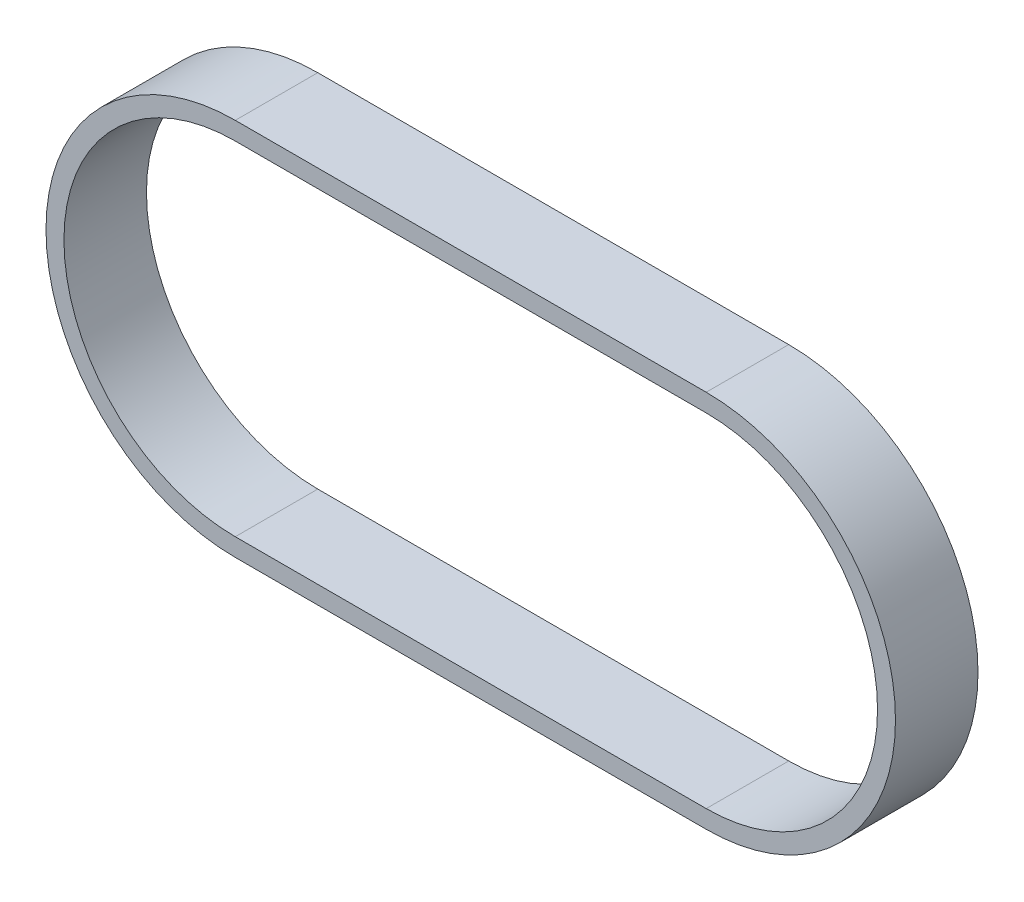
SolidWorks part; units mm, degrees
ref_plane "Front Plane" through (0, 0, 0) normal (0, 0, 1) x (1, 0, 0)
ref_plane "Top Plane" through (0, 0, 0) normal (0, 1, 0) x (1, 0, 0)
ref_plane "Right Plane" through (0, 0, 0) normal (1, 0, 0) x (0, 0, -1)
sketch "Sketch1" plane through (0, 0, 0) normal (0, 0, 1) x (1, 0, 0)
  line L0 (0, 0) -> (52.5, 0) construction
  line L1 (0, 19.1) -> (52.5, 19.1)
  line L2 (0, -19.1) -> (52.5, -19.1)
  circle A0 centre (0, 0) radius 19.1 construction
  circle A1 centre (52.5, 0) radius 19.1 construction
  arc A2 (52.5, -19.1) -> (52.5, 19.1) centre (52.5, 0) ccw
  arc A3 (0, 19.1) -> (0, -19.1) centre (0, 0) ccw
  dimension "D2" = 38.2
  dimension "D1" = 52.5
extrude "Extrude-Thin1" add sketch "Sketch1" along normal blind 9.2 thin thin type one direction wall 2
equation "\"pitchDiameter\"= 38.2mm"
equation "\"pulley2pulleyDistance\" = 52.5mm"
equation "\"D1@Sketch1\"=\"pulley2pulleyDistance\""
equation "\"D2@Sketch1\"=\"pitchDiameter\""
